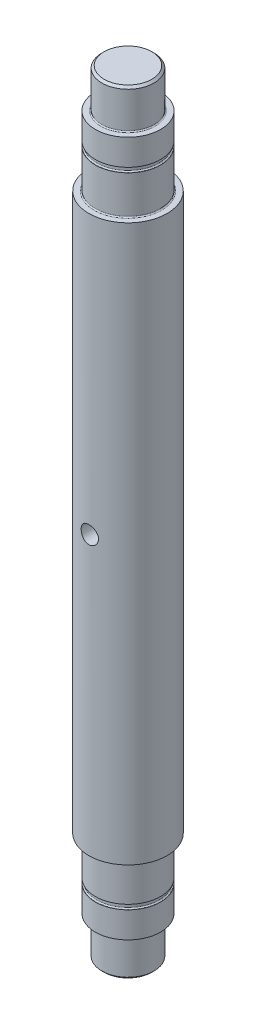
SolidWorks part; units mm, degrees
material "Plain Carbon Steel"
ref_plane "Front Plane" through (0, 0, 0) normal (0, 0, 1) x (1, 0, 0)
ref_plane "Top Plane" through (0, 0, 0) normal (0, 1, 0) x (1, 0, 0)
ref_plane "Right Plane" through (0, 0, 0) normal (1, 0, 0) x (0, 0, -1)
sketch "Sketch1" plane through (0, 0, 0) normal (0, 0, 1) x (1, 0, 0)
  line L0 (0, 63.2573) -> (0, -62.094) construction
  line L1 (0, -44.7868) -> (0, 44.7868) construction
  line L2 (0, 89) -> (6, 89)
  line L4 (7.5, 64) -> (9, 64)
  line L5 (9, 64) -> (9, -64)
  line L6 (9, -64) -> (7.5, -64)
  line L9 (0, -89) -> (0, 89)
  line L18 (6, 80) -> (7.5, 80)
  line L19 (7.5, 80) -> (7.5, 74)
  line L20 (7.5, -64) -> (7.5, -72.9)
  line L21 (7.5, -80) -> (6, -80)
  line L22 (55, 0) -> (-55, 0) construction
  line L23 (7.5, 74) -> (7.15, 74)
  line L24 (7.15, 74) -> (7.15, 72.9)
  line L25 (7.15, 72.9) -> (7.5, 72.9)
  line L26 (6, 89) -> (6, 80)
  line L27 (7.5, 72.9) -> (7.5, 64)
  line L28 (6, -80) -> (6, -89)
  line L29 (6, -89) -> (0, -89)
  line L30 (7.5, -72.9) -> (7.15, -72.9)
  line L31 (7.15, -72.9) -> (7.15, -74)
  line L32 (7.15, -74) -> (7.5, -74)
  line L33 (7.5, -74) -> (7.5, -80)
  point P7 (9, 0)
  dimension "D2" = 9
  dimension "D3" = 6
  dimension "D4" = 9
  dimension "D5" = 10
  dimension "D6" = 7.15
  dimension "D7" = 1.1
  dimension "D8" = 9
  dimension "D9" = 1.1
  dimension "D10" = 7.15
  dimension "D11" = 16
  dimension "D12" = 7.5
  dimension "D13" = 10
  dimension "D14" = 16
  dimension "D15" = 128
revolve "Revolve1" add sketch "Sketch1" angle 360 about L0
sketch "Sketch3" plane through (0, 0, 0) normal (0, 0, 1) x (1, 0, 0)
  line L5 (0, -2) -> (0, 2) construction
  circle A1 centre (0, 0) radius 2
  dimension "D1" = 4
extrude "Cut-Extrude2" cut sketch "Sketch3" against normal through all both and the other way through all
fillet "Fillet1" radius 0.25 8 edges at (0, 64, 7.5) (0, -64, 7.5) (0, 80, 6) (0, -80, 6) (0, -74, 7.15) (0, -72.9, 7.15) (0, 72.9, 7.15) (0, 74, 7.15)
chamfer "Chamfer1" distance 0.5 angle 45 2 edges at (0, 89, 6) (0, -89, 6)
